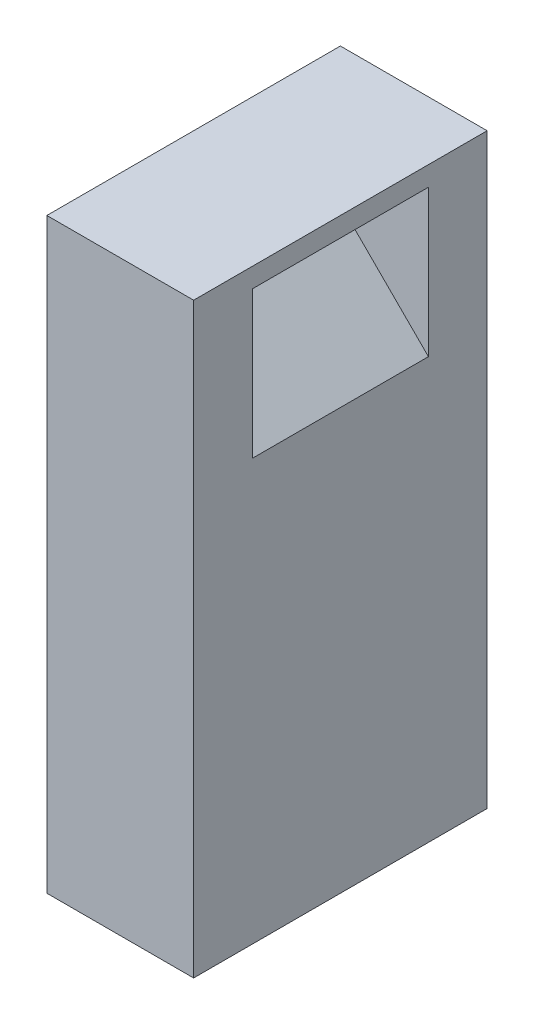
SolidWorks part; units mm, degrees
ref_plane "Front Plane" through (0, 0, 0) normal (0, 0, 1) x (1, 0, 0)
ref_plane "Top Plane" through (0, 0, 0) normal (0, 1, 0) x (1, 0, 0)
ref_plane "Right Plane" through (0, 0, 0) normal (1, 0, 0) x (0, 0, -1)
sketch "Sketch1" plane through (0, 0, 0) normal (0, 0, 1) x (1, 0, 0)
  line L1 (0, 0) -> (75, 0)
  line L2 (0, 0) -> (0, 300)
  line L3 (0, 300) -> (75, 300)
  line L4 (75, 0) -> (75, 300)
  dimension "D1" = 300
  dimension "D2" = 75
extrude "Boss-Extrude1" add sketch "Sketch1" along normal mid plane 150
sketch "Sketch2" plane through (0, 0, 75) normal (0, 0, 1) x (1, 0, 0)
  line L0 (75, 290) -> (37.5, 252.5)
  line L1 (75, 0) -> (75, 300) construction
  line L2 (37.5, 252.5) -> (75, 215)
  line L3 (0, 300) -> (0, 0) construction
  line L4 (75, 300) -> (0, 300) construction
  line L5 (75, 290) -> (75, 215)
  dimension "D1" = 10
  dimension "D2" = 37.5
  dimension "D3" = 45
extrude "Cut-Extrude1" cut sketch "Sketch2" against normal mid plane 90 from offset 75
